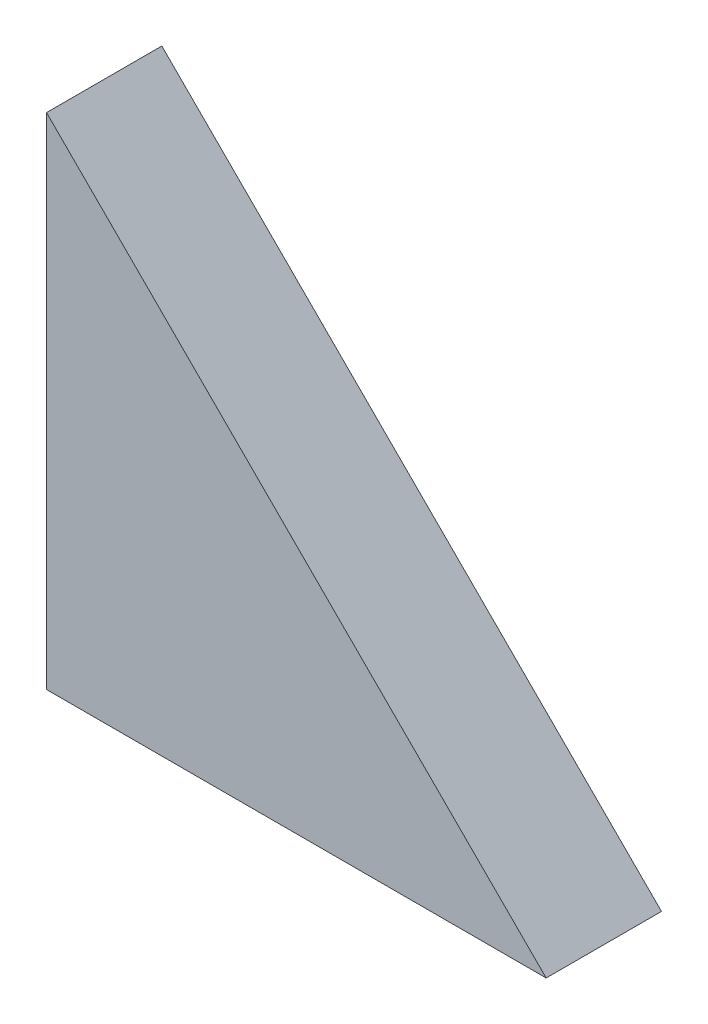
SolidWorks part; units mm, degrees
material "Balsa"
ref_plane "Front Plane" through (0, 0, 0) normal (0, 0, 1) x (1, 0, 0)
ref_plane "Top Plane" through (0, 0, 0) normal (0, 1, 0) x (1, 0, 0)
ref_plane "Right Plane" through (0, 0, 0) normal (1, 0, 0) x (0, 0, -1)
sketch "Sketch1" plane through (0, 0, 0) normal (0, 0, 1) x (1, 0, 0)
  line L0 (0, 0) -> (0, 165.1)
  line L1 (0, 165.1) -> (165.1, 0)
  line L2 (165.1, 0) -> (0, 0)
  dimension "D1" = 90
  dimension "D2" = 45
  dimension "D3" = 233.4867
extrude "Boss-Extrude1" add sketch "Sketch1" along normal blind 38.1
